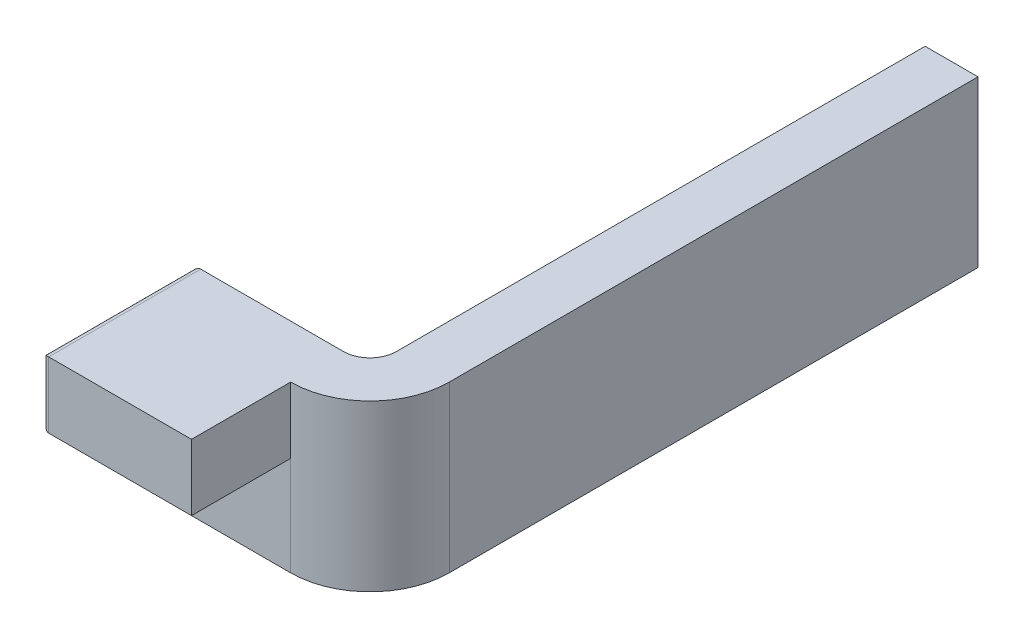
SolidWorks part; units mm, degrees
ref_plane "前视基准面" through (0, 0, 0) normal (0, 0, 1) x (1, 0, 0)
ref_plane "上视基准面" through (0, 0, 0) normal (0, 1, 0) x (1, 0, 0)
ref_plane "右视基准面" through (0, 0, 0) normal (1, 0, 0) x (0, 0, -1)
other "Configuration Table"
sketch "草图1" plane through (0, 0, 0) normal (0, 1, 0) x (1, 0, 0)
  line L0 (0, 0) -> (22.6, 0)
  line L1 (26.6, 4) -> (26.6, 84)
  line L2 (0, -8) -> (22.6, -8)
  line L3 (34.6, 4) -> (34.6, 84)
  line L4 (26.6, 84) -> (34.6, 84)
  line L6 (0, 0) -> (0, -8)
  line L7 (0, 0) -> (22.6, 0) construction
  line L8 (0, -8) -> (22.6, -8) construction
  arc A0 (22.6, 0) -> (26.6, 4) centre (22.6, 4) ccw
  arc A1 (22.6, -8) -> (34.6, 4) centre (22.6, 4) ccw
  dimension "D2" = 8
  dimension "D3" = 4
  dimension "D1" = 22.6
  dimension "D4" = 80
extrude "凸台-拉伸1" add sketch "草图1" along normal blind 25
sketch "草图2" plane through (0, 0, 8) normal (0, 0, 1) x (1, 0, 0)
  line L0 (22.6, 25) -> (22.6, 0) construction
  line L1 (0, 25) -> (22.6, 25)
  line L2 (0, 25) -> (0, 15)
  line L3 (0, 15) -> (22.6, 15)
  line L4 (22.6, 25) -> (22.6, 15)
  dimension "D1" = 10
extrude "凸台-拉伸2" add sketch "草图2" along normal blind 15
fillet "圆角1" radius 1 5 edges at (0, 20, 23) (0, 25, 11.5) (0, 15, 15.5) (0, 7.5, 8) (0, 12.5, 0)
